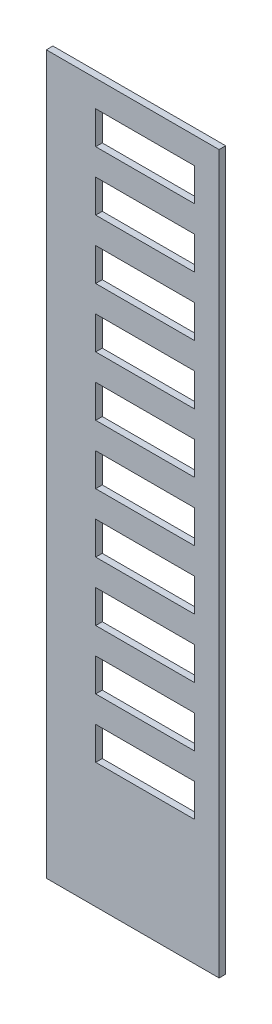
SolidWorks part; units mm, degrees
ref_plane "Front Plane" through (0, 0, 0) normal (0, 0, 1) x (1, 0, 0)
ref_plane "Top Plane" through (0, 0, 0) normal (0, 1, 0) x (1, 0, 0)
ref_plane "Right Plane" through (0, 0, 0) normal (1, 0, 0) x (0, 0, -1)
sketch "Sketch2" plane through (0, 0, 0) normal (0, 0, 1) x (1, 0, 0)
  line L0 (-22.5, -94) -> (-7.5, -94)
  line L1 (-22.5, -94) -> (30, -94)
  line L2 (-22.5, -94) -> (-22.5, 94)
  line L3 (-22.5, 94) -> (30, 94)
  line L4 (30, -94) -> (30, 94)
  line L5 (3.75, 94) -> (3.75, -94) construction
  line L6 (-22.5, 0) -> (30, 0) construction
  line L7 (-7.5, -94) -> (22.5, -94)
  line L8 (-22.5, -94) -> (-22.5, -86)
  line L9 (-22.5, -86) -> (-22.5, -76)
  line L10 (-22.5, -76) -> (-22.5, -68)
  line L11 (-22.5, -68) -> (-22.5, -58)
  line L12 (-22.5, -58) -> (-22.5, -50)
  line L13 (-22.5, -50) -> (-22.5, -40)
  line L14 (-22.5, -40) -> (-22.5, -32)
  line L15 (-22.5, -32) -> (-22.5, -22)
  line L16 (-22.5, -22) -> (-22.5, -14)
  line L17 (-22.5, -14) -> (-22.5, -4)
  line L18 (-22.5, -4) -> (-22.5, 4)
  line L19 (-22.5, 4) -> (-22.5, 14)
  line L20 (-22.5, 14) -> (-22.5, 22)
  line L21 (-22.5, 22) -> (-22.5, 32)
  line L22 (-22.5, 32) -> (-22.5, 40)
  line L23 (-22.5, 40) -> (-22.5, 50)
  line L24 (-22.5, 50) -> (-22.5, 58)
  line L25 (-22.5, 58) -> (-22.5, 68)
  line L26 (-22.5, 68) -> (-22.5, 76)
  line L27 (-22.5, 76) -> (-22.5, 86)
  line L28 (-7.5, -94) -> (-7.5, 94)
  line L29 (22.5, -94) -> (22.5, 94)
  line L30 (-22.5, -86) -> (30, -86)
  line L31 (-22.5, -76) -> (30, -76)
  line L32 (-22.5, -68) -> (30, -68)
  line L33 (-22.5, -58) -> (30, -58)
  line L34 (-22.5, -50) -> (30, -50)
  line L35 (-22.5, -40) -> (30, -40)
  line L36 (30, -40) -> (-22.5, -40)
  line L37 (-22.5, -32) -> (30, -32)
  line L38 (-22.5, -22) -> (30, -22)
  line L39 (-22.5, -14) -> (30, -14)
  line L40 (-22.5, -4) -> (30, -4)
  line L41 (-22.5, 4) -> (30, 4)
  line L42 (-22.5, 14) -> (30, 14)
  line L43 (-22.5, 22) -> (30, 22)
  line L44 (-22.5, 32) -> (30, 32)
  line L45 (-22.5, 40) -> (30, 40)
  line L46 (-22.5, 50) -> (30, 50)
  line L47 (-22.5, 58) -> (30, 58)
  line L48 (-22.5, 68) -> (30, 68)
  line L49 (-22.5, 76) -> (30, 76)
  line L50 (-22.5, 86) -> (30, 86)
  point P0 (3.75, 0)
  dimension "D1" = 188
  dimension "D2" = 52.5
  dimension "D3" = 15
  dimension "D4" = 7.5
  dimension "D5" = 30
  dimension "D6" = 8
  dimension "D7" = 10
  dimension "D8" = 8
  dimension "D9" = 10
  dimension "D10" = 8
  dimension "D11" = 10
  dimension "D12" = 8
  dimension "D13" = 10
  dimension "D14" = 8
  dimension "D15" = 10
  dimension "D16" = 8
  dimension "D17" = 10
  dimension "D18" = 8
  dimension "D19" = 10
  dimension "D20" = 8
  dimension "D21" = 10
  dimension "D22" = 8
  dimension "D23" = 10
  dimension "D24" = 8
  dimension "D25" = 10
  dimension "D26" = 8
extrude "Boss-Extrude1" add sketch "Sketch2" along normal blind 2 contours L2 L50 L28 L3 | L28 L50 L29 L3 | L29 L50 L4 L3 | L50 L29 L49 L4 | L49 L29 L48 L4 | L49 L28 L48 L29 | L49 L2 L48 L28 | L50 L2 L49 L28 | L48 L2 L47 L28 | L47 L2 L46 L28 | L47 L28 L46 L29 | L47 L29 L46 L4 | L48 L29 L47 L4 | L46 L2 L45 L28 | L45 L2 L44 L28 | L44 L2 L43 L28 | L30 L2 L0 L28 | L30 L28 L1 L29 | L30 L29 L1 L4 | L31 L29 L30 L4 | L31 L2 L30 L28 | L32 L2 L31 L28 | L32 L28 L31 L29 | L32 L29 L31 L4 | L33 L29 L32 L4 | L34 L29 L33 L4 | L34 L28 L33 L29 | L34 L2 L33 L28 | L33 L2 L32 L28 | L35 L2 L34 L28 | L37 L2 L35 L28 | L38 L2 L37 L28 | L39 L2 L38 L28 | L40 L2 L39 L28 | L37 L28 L35 L29 | L37 L29 L35 L4 | L35 L29 L34 L4 | L38 L29 L37 L4 | L39 L29 L38 L4 | L39 L28 L38 L29 | L40 L29 L39 L4 | L41 L2 L40 L28 | L41 L28 L40 L29 | L41 L29 L40 L4 | L42 L29 L41 L4 | L42 L2 L41 L28 | L43 L2 L42 L28 | L45 L28 L44 L29 | L43 L28 L42 L29 | L43 L29 L42 L4 | L44 L29 L43 L4 | L45 L29 L44 L4 | L46 L29 L45 L4
sketch "Sketch3" plane through (0, 0, 2) normal (0, 0, 1) x (1, 0, 0)
  line L1 (-22.5, -94) -> (30, -94)
  line L2 (-22.5, -94) -> (-22.5, -124)
  line L3 (-22.5, -124) -> (30, -124)
  line L4 (30, -94) -> (30, -124)
  dimension "D1" = 30
  dimension "D2" = 52.5
extrude "Boss-Extrude2" add sketch "Sketch3" against normal blind 2
